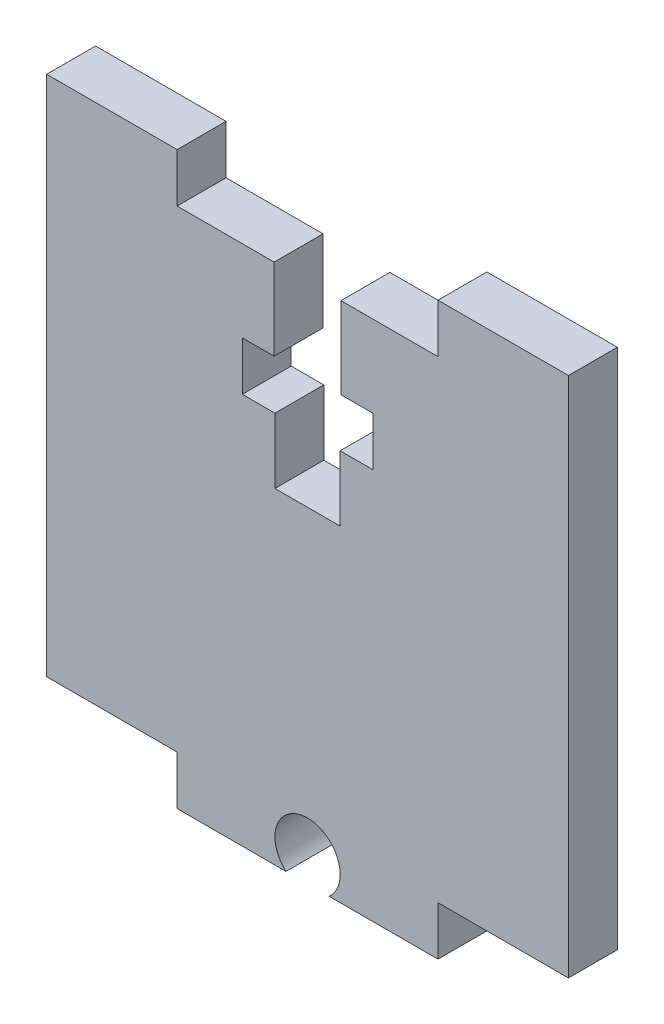
SolidWorks part; units mm, degrees
ref_plane "前视" through (0, 0, 0) normal (0, 0, 1) x (1, 0, 0)
ref_plane "上视" through (0, 0, 0) normal (0, 1, 0) x (1, 0, 0)
ref_plane "右视" through (0, 0, 0) normal (1, 0, 0) x (0, 0, -1)
sketch "草图2" plane through (0, 0, 0) normal (0, 0, 1) x (1, 0, 0)
  line L0 (0, 103.0974) -> (0, -63.3868) construction
  line L1 (2.0479, 48.8553) -> (8, 48.8553)
  line L2 (8, 48.8553) -> (8, 51.8553)
  line L3 (8, 51.8553) -> (16, 51.8553)
  line L4 (16, 51.8553) -> (16, 19.8553)
  line L5 (16, 19.8553) -> (8, 19.8553)
  line L6 (2.0479, 48.8553) -> (2.0479, 43.8553)
  line L7 (2.0479, 43.8553) -> (4, 43.8553)
  line L8 (4, 43.8553) -> (4, 40.8553)
  line L9 (4, 40.8553) -> (2, 40.8553)
  line L10 (2, 40.8553) -> (2, 36.8553)
  line L11 (2, 36.8553) -> (-2, 36.8553)
  line L12 (1.3229, 16.8553) -> (8, 16.8553)
  line L13 (8, 16.8553) -> (8, 19.8553)
  line L14 (-8, 16.8553) -> (-8, 19.8553)
  line L15 (-1.3229, 16.8553) -> (-8, 16.8553)
  line L16 (-2, 40.8553) -> (-2, 36.8553)
  line L17 (-4, 40.8553) -> (-2, 40.8553)
  line L18 (-4, 43.8553) -> (-4, 40.8553)
  line L19 (-2.0479, 43.8553) -> (-4, 43.8553)
  line L20 (-2.0479, 48.8553) -> (-2.0479, 43.8553)
  line L21 (-16, 19.8553) -> (-8, 19.8553)
  line L22 (-16, 51.8553) -> (-16, 19.8553)
  line L23 (-8, 51.8553) -> (-16, 51.8553)
  line L24 (-8, 48.8553) -> (-8, 51.8553)
  line L25 (-2.0479, 48.8553) -> (-8, 48.8553)
  arc A0 (1.3229, 16.8553) -> (-1.3229, 16.8553) centre (0, 18.3553) ccw
  point P22 (0, 36.8553)
  dimension "D12" = 4
  dimension "D1" = 8
  dimension "D2" = 8
  dimension "D3" = 3
  dimension "D4" = 12
  dimension "D5" = 5
  dimension "D6" = 3
  dimension "D7" = 2
  dimension "D8" = 2
  dimension "D9" = 32
  dimension "D10" = 3
extrude "凸台-拉伸1" add sketch "草图2" along normal blind 3
